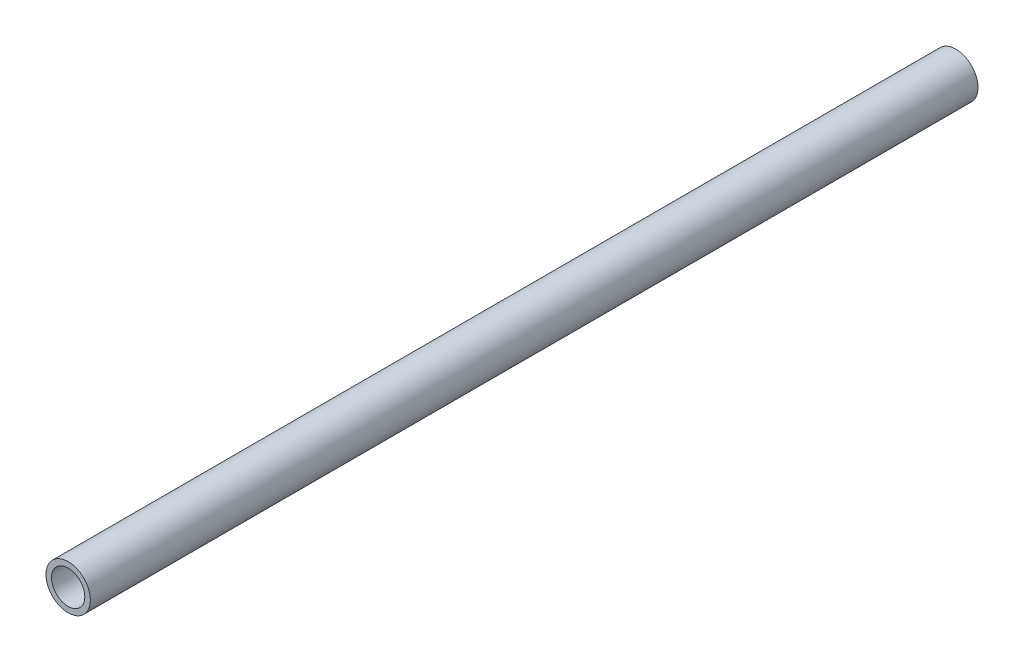
SolidWorks part; units mm, degrees
material "Pine"
ref_plane "Front Plane" through (0, 0, 0) normal (0, 0, 1) x (1, 0, 0)
ref_plane "Top Plane" through (0, 0, 0) normal (0, 1, 0) x (1, 0, 0)
ref_plane "Right Plane" through (0, 0, 0) normal (1, 0, 0) x (0, 0, -1)
sketch "Sketch1" plane through (0, 0, 0) normal (0, 0, 1) x (1, 0, 0)
  circle A0 centre (0, 0) radius 6.35
  circle A1 centre (0, 0) radius 4.7625
  dimension "D1" = 12.7
  dimension "D2" = 9.525
extrude "Boss-Extrude1" add sketch "Sketch1" along normal mid plane 254
equation "\"D2@Sketch1\"=0.50 - (1/8)"
